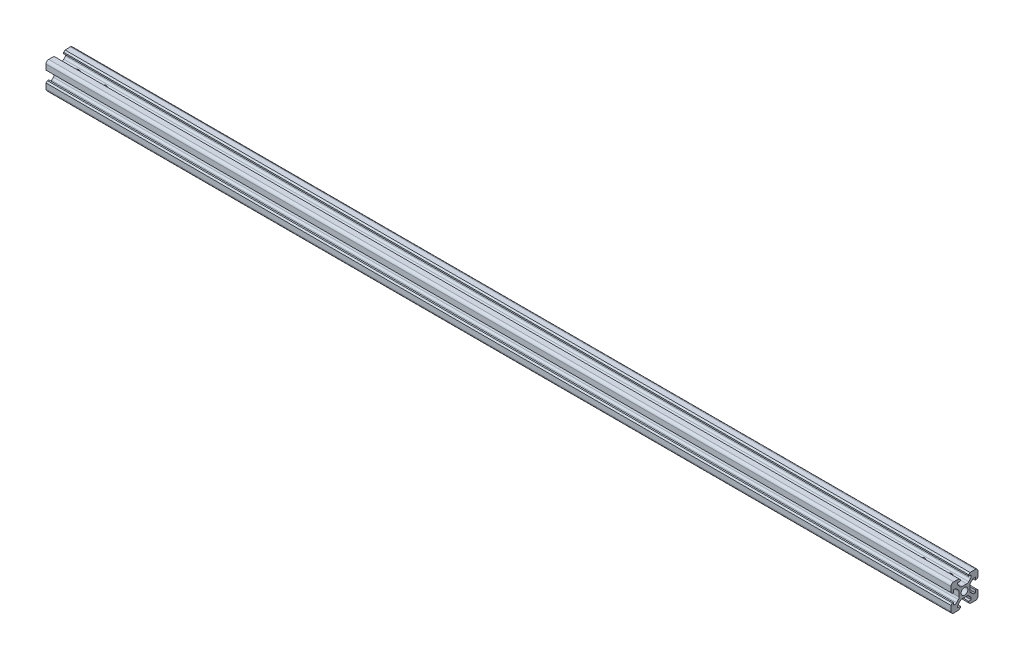
SolidWorks part; units mm, degrees
ref_plane "Front Plane" through (0, 0, 0) normal (0, 0, 1) x (1, 0, 0)
ref_plane "Top Plane" through (0, 0, 0) normal (0, 1, 0) x (1, 0, 0)
ref_plane "Right Plane" through (0, 0, 0) normal (1, 0, 0) x (0, 0, -1)
sketch "Sketch1" plane through (0, 0, 0) normal (1, 0, 0) x (0, 0, -1)
  line B0 (-4.1, 10) -> (-8, 10)
  line B1 (-3.1, 8) -> (-3.1, 9)
  line B2 (9, -3.1) -> (10, -4.1)
  line B3 (3.1, 8) -> (3.1, 9)
  line B4 (4.4142, 5.8284) -> (3.1236, 4.5379)
  line B5 (10, 4.1) -> (9, 3.1)
  line B6 (5, 8) -> (3.1, 8)
  line B7 (5, 7.2426) -> (5, 8)
  line B8 (-3.1, 8) -> (-5, 8)
  line B9 (-5, 7.2426) -> (-5, 8)
  line B10 (4.1, 10) -> (3.1, 9)
  line B11 (5.8284, -4.4142) -> (4.5379, -3.1236)
  line B12 (7.2426, -5) -> (8, -5)
  line B13 (8, -3.1) -> (8, -5)
  line B14 (7.2426, 5) -> (8, 5)
  line B15 (8, 10) -> (4.1, 10)
  line B16 (-1.7094, 3.9521) -> (1.7094, 3.9521)
  line B17 (8, 5) -> (8, 3.1)
  line B18 (8, 3.1) -> (9, 3.1)
  line B19 (-3.1, 9) -> (-4.1, 10)
  line B20 (8, -3.1) -> (9, -3.1)
  line B21 (3.9521, 1.7094) -> (3.9521, -1.7094)
  line B22 (-3.1236, 4.5379) -> (-4.4142, 5.8284)
  line B23 (10, -4.1) -> (10, -8)
  line B24 (4.5379, 3.1236) -> (5.8284, 4.4142)
  line B25 (-3.1, -9) -> (-4.1, -10)
  line B26 (8, -10) -> (4.1, -10)
  line B27 (4.1, -10) -> (3.1, -9)
  line B28 (-4.4142, -5.8284) -> (-3.1236, -4.5379)
  line B29 (-5, -7.2426) -> (-5, -8)
  line B30 (-3.1, -8) -> (-5, -8)
  line B31 (5, -7.2426) -> (5, -8)
  line B32 (5, -8) -> (3.1, -8)
  line B33 (3.1, -8) -> (3.1, -9)
  line B34 (-3.1, -8) -> (-3.1, -9)
  line B35 (1.7094, -3.9521) -> (-1.7094, -3.9521)
  line B36 (-4.1, -10) -> (-8, -10)
  line B37 (3.1236, -4.5379) -> (4.4142, -5.8284)
  line B38 (-9, 3.1) -> (-10, 4.1)
  line B39 (-10, -8) -> (-10, -4.1)
  line B40 (-10, -4.1) -> (-9, -3.1)
  line B41 (-5.8284, 4.4142) -> (-4.5379, 3.1236)
  line B42 (-7.2426, 5) -> (-8, 5)
  line B43 (-8, 3.1) -> (-8, 5)
  line B44 (-7.2426, -5) -> (-8, -5)
  line B45 (-8, -5) -> (-8, -3.1)
  line B46 (-8, -3.1) -> (-9, -3.1)
  line B47 (-8, 3.1) -> (-9, 3.1)
  line B48 (-3.9521, -1.7094) -> (-3.9521, 1.7094)
  line B49 (-10, 8) -> (-10, 4.1)
  line B50 (-4.5379, -3.1236) -> (-5.8284, -4.4142)
  line B51 (10, 8) -> (10, 4.1)
  circle B52 centre (0, 0) radius 2.5
  arc B53 (-4.5379, 3.1236) -> (-3.9521, 1.7094) centre (-5.9521, 1.7094) cw
  arc B54 (-5.8284, 4.4142) -> (-7.2426, 5) centre (-7.2426, 3) ccw
  arc B55 (-5, 7.2426) -> (-4.4142, 5.8284) centre (-3, 7.2426) ccw
  arc B56 (5, 7.2426) -> (4.4142, 5.8284) centre (3, 7.2426) cw
  arc B57 (7.2426, 5) -> (5.8284, 4.4142) centre (7.2426, 3) ccw
  arc B58 (5.8284, -4.4142) -> (7.2426, -5) centre (7.2426, -3) ccw
  arc B59 (5, -7.2426) -> (4.4142, -5.8284) centre (3, -7.2426) ccw
  arc B60 (-4.4142, -5.8284) -> (-5, -7.2426) centre (-3, -7.2426) ccw
  arc B61 (-7.2426, -5) -> (-5.8284, -4.4142) centre (-7.2426, -3) ccw
  arc B62 (-3.9521, -1.7094) -> (-4.5379, -3.1236) centre (-5.9521, -1.7094) cw
  arc B63 (-3.1236, -4.5379) -> (-1.7094, -3.9521) centre (-1.7094, -5.9521) cw
  arc B64 (1.7094, -3.9521) -> (3.1236, -4.5379) centre (1.7094, -5.9521) cw
  arc B65 (4.5379, -3.1236) -> (3.9521, -1.7094) centre (5.9521, -1.7094) cw
  arc B66 (3.9521, 1.7094) -> (4.5379, 3.1236) centre (5.9521, 1.7094) cw
  arc B67 (1.7094, 3.9521) -> (3.1236, 4.5379) centre (1.7094, 5.9521) ccw
  arc B68 (-1.7094, 3.9521) -> (-3.1236, 4.5379) centre (-1.7094, 5.9521) cw
  arc B69 (10, 8) -> (8, 10) centre (8, 8) ccw
  arc B70 (-8, -10) -> (-10, -8) centre (-8, -8) cw
  arc B71 (10, -8) -> (8, -10) centre (8, -8) cw
  arc B72 (-8, 10) -> (-10, 8) centre (-8, 8) ccw
sketch_block_instance "2020-1"
sketch_block "2020" parameters "D1"=2
extrude "Boss-Extrude1" add sketch "Sketch1" along normal blind 670
sketch "Sketch2" plane through (0, 10, 0) normal (0, 1, 0) x (1, 0, 0)
  line L0 (670, 0) -> (658, 0) construction
  line L2 (335, 10) -> (335, 39.1742) construction
  line L3 (670, 10) -> (0, 10) construction
  line L4 (670, 1.7094) -> (670, -1.7094) construction
  circle A0 centre (658, 0) radius 2.5
  circle A1 centre (638, 0) radius 2.5
  circle A2 centre (32, 0) radius 2.5
  circle A3 centre (12, 0) radius 2.5
  dimension "D1" = 2
  dimension "D2" = 20
  dimension "D3" = 12
extrude "Cut-Extrude1" cut sketch "Sketch2" against normal through all
